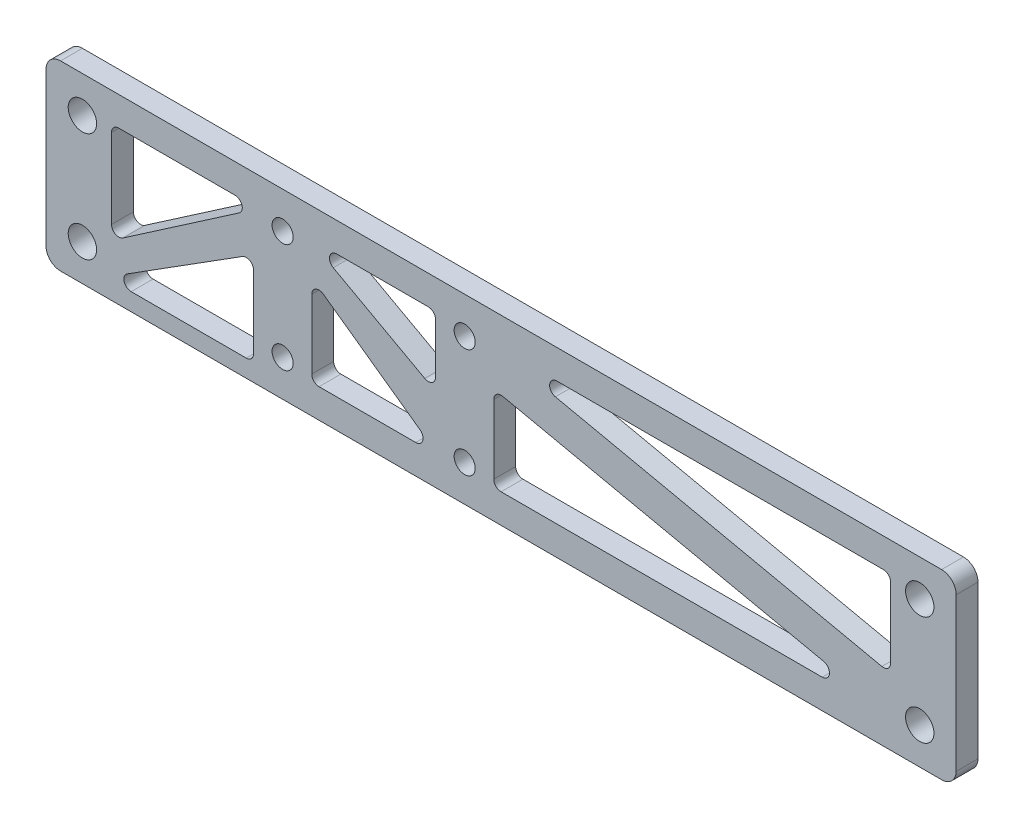
SolidWorks part; units mm, degrees
material "Thornel Mat VMA"
ref_plane "前视基准面" through (0, 0, 0) normal (0, 0, 1) x (1, 0, 0)
ref_plane "上视基准面" through (0, 0, 0) normal (0, 1, 0) x (1, 0, 0)
ref_plane "右视基准面" through (0, 0, 0) normal (1, 0, 0) x (0, 0, -1)
sketch "草图1" plane through (0, 0, 0) normal (0, 0, 1) x (1, 0, 0)
  line L1 (0, 0) -> (125, 0)
  line L2 (0, 0) -> (0, 25)
  line L3 (0, 25) -> (125, 25)
  line L4 (125, 0) -> (125, 25)
  line L5 (32.5, 20) -> (57.5, 20) construction
  line L6 (32.5, 20) -> (32.5, 5) construction
  line L7 (32.5, 5) -> (57.5, 5) construction
  line L8 (57.5, 20) -> (57.5, 5) construction
  line L9 (57.5, 12.5) -> (125, 12.5) construction
  circle A0 centre (32.5, 20) radius 1.45
  circle A1 centre (57.5, 20) radius 1.45
  circle A2 centre (57.5, 5) radius 1.45
  circle A3 centre (32.5, 5) radius 1.45
  circle A4 centre (5, 20) radius 1.95
  circle A5 centre (5, 5) radius 1.95
  circle A6 centre (120, 20) radius 1.95
  circle A7 centre (120, 5) radius 1.95
  dimension "D4" = 2.9
  dimension "D5" = 2.9
  dimension "D6" = 2.9
  dimension "D7" = 2.9
  dimension "D10" = 3.9
  dimension "D11" = 3.9
  dimension "D12" = 3.9
  dimension "D13" = 3.9
  dimension "D14" = 5
  dimension "D15" = 5
  dimension "D16" = 5
  dimension "D17" = 5
  dimension "D18" = 5
  dimension "D20" = 5
  dimension "D21" = 5
  dimension "D22" = 115
  dimension "D9" = 27.5
  dimension "D2" = 25
  dimension "D3" = 15
  dimension "D8" = 25
  dimension "D19" = 5
extrude "凸台-拉伸1" add sketch "草图1" along normal blind 3
sketch "草图2" plane through (0, 0, 3) normal (0, 0, 1) x (1, 0, 0)
  line L0 (60.7678, 21) -> (116, 21)
  line L1 (116, 21) -> (116, 9.1145)
  line L2 (116, 9.1145) -> (60.7678, 21)
  line L3 (61.5, 15.728) -> (61.5, 4)
  line L4 (61.5, 4) -> (116, 4)
  line L5 (116, 4) -> (61.5, 15.728)
  line L6 (36.0222, 21) -> (53.5, 21)
  line L7 (53.5, 21) -> (53.5, 11.4254)
  line L8 (53.5, 11.4254) -> (36.0222, 21)
  line L9 (36.5, 16.4323) -> (36.5, 4)
  line L10 (36.5, 4) -> (53.904, 4)
  line L11 (53.904, 4) -> (36.5, 16.4323)
  line L12 (125, 25) -> (0, 25) construction
  line L13 (0, 0) -> (125, 0) construction
  line L14 (29.1801, 21) -> (9, 21)
  line L15 (9, 21) -> (9, 7.1445)
  line L16 (9, 7.1445) -> (29.1801, 21)
  line L17 (28.5, 15.1836) -> (28.5, 2.402)
  line L18 (28.5, 2.402) -> (8.2395, 2.402)
  line L19 (8.2395, 2.402) -> (28.5, 15.1836)
  circle A0 centre (57.5, 5) radius 1.45 construction
  circle A1 centre (120, 20) radius 1.95 construction
  circle A2 centre (32.5, 5) radius 1.45 construction
  circle A3 centre (57.5, 20) radius 1.45 construction
  circle A4 centre (5, 20) radius 1.95 construction
  point P16 (28.0073, 21)
  point P17 (8.5866, 1.3984)
  point P30 (26.0132, 2.8723)
  point P31 (28.0073, 15.1836)
  point P34 (8.2395, 2.402)
  point P35 (29.1801, 21)
  dimension "D6" = 4
  dimension "D9" = 4
  dimension "D1" = 4
  dimension "D2" = 4
  dimension "D3" = 5
  dimension "D4" = 4
  dimension "D5" = 4
  dimension "D7" = 4
  dimension "D8" = 4
  dimension "D10" = 4
  dimension "D11" = 4
extrude "切除-拉伸1" cut sketch "草图2" against normal blind 10
fillet "圆角1" radius 2 4 edges at (125, 0, 1.5) (125, 25, 1.5) (0, 0, 1.5) (0, 25, 1.5)
fillet "圆角2" radius 1 18 edges at (60.7678, 21, 1.5) (116, 21, 1.5) (116, 9.1145, 1.5) (28.5, 15.1836, 1.5) (28.5, 2.402, 1.5) (8.2395, 2.402, 1.5) (116, 4, 1.5) (61.5, 15.728, 1.5) (36.0222, 21, 1.5) (53.5, 21, 1.5) (53.5, 11.4254, 1.5) (53.904, 4, 1.5) (36.5, 4, 1.5) (36.5, 16.4323, 1.5) (9, 7.1445, 1.5) (9, 21, 1.5) (29.1801, 21, 1.5) (61.5, 4, 1.5)
